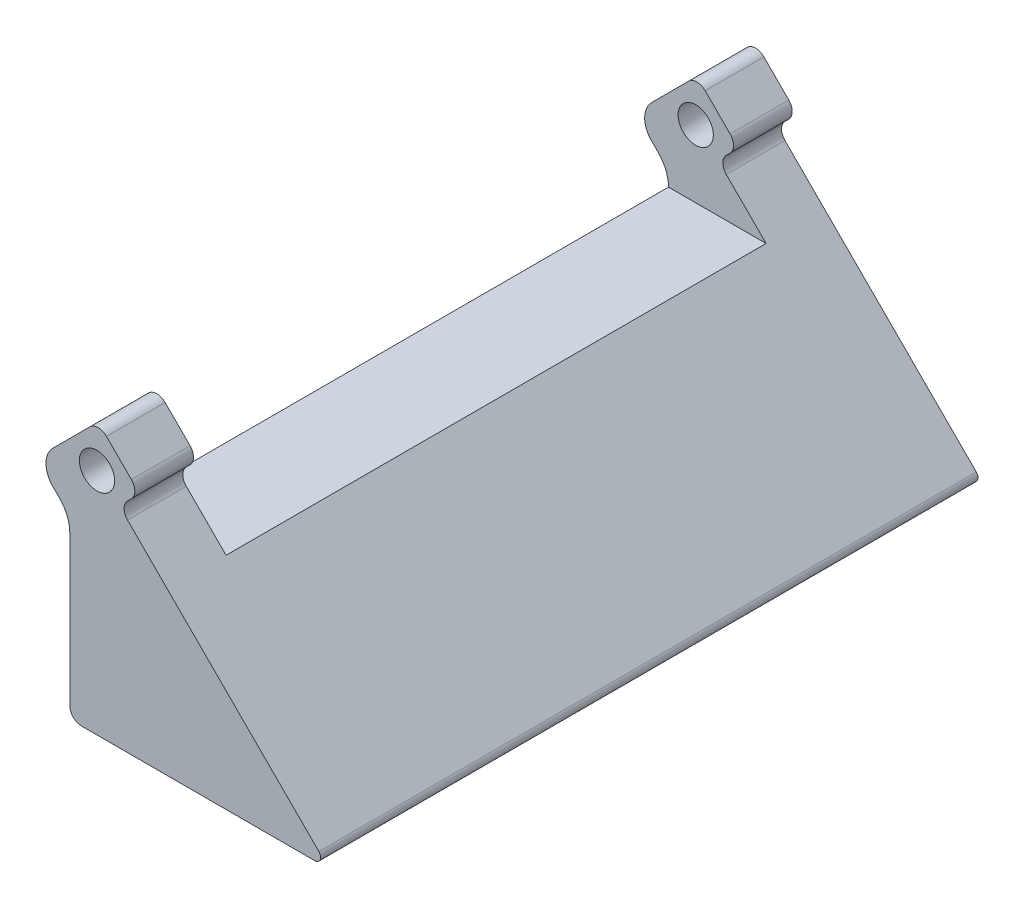
SolidWorks part; units mm, degrees
material "1060-H12"
ref_plane "Front Plane" through (0, 0, 0) normal (0, 0, 1) x (1, 0, 0)
ref_plane "Top Plane" through (0, 0, 0) normal (0, 1, 0) x (1, 0, 0)
ref_plane "Right Plane" through (0, 0, 0) normal (1, 0, 0) x (0, 0, -1)
sketch "Sketch1" plane through (0, 0, 0) normal (0, 0, 1) x (1, 0, 0)
  line L0 (30.0967, -21) -> (76.9648, -21)
  line L1 (-1.3178, -19.5) -> (18.5462, -19.5)
  line L2 (-9.1152, 9.3685) -> (-1.6411, 1.8944)
  line L3 (2.6015, -0.934) -> (2.9274, -0.6081)
  line L4 (2.9274, 0.8061) -> (0.8061, 2.9274)
  line L5 (-0.6081, 2.9274) -> (-1.6411, 1.8944)
  line L6 (-1.6411, 1.8944) -> (-3.7625, -0.2269)
  line L7 (-3.7625, -3.0553) -> (-3.1965, -3.6213)
  line L8 (-2.3178, -5.7426) -> (-2.3178, -18.5)
  line L9 (2.6015, -2.3482) -> (18.8997, -18.6464)
  circle A0 centre (0, 0) radius 1.5
  circle A1 centre (30.0967, 0.35) radius 21.35
  arc A2 (2.9274, -0.6081) -> (2.9274, 0.8061) centre (2.2203, 0.099) ccw
  arc A3 (0.8061, 2.9274) -> (-0.6081, 2.9274) centre (0.099, 2.2203) ccw
  arc A4 (-2.3178, -18.5) -> (-1.3178, -19.5) centre (-1.3178, -18.5) ccw
  arc A5 (2.6015, -0.934) -> (2.6015, -2.3482) centre (3.3086, -1.6411) ccw
  arc A6 (-3.7625, -0.2269) -> (-3.7625, -3.0553) centre (-2.3482, -1.6411) ccw
  arc A7 (18.5462, -19.5) -> (18.8997, -18.6464) centre (18.5462, -19) ccw
  arc A8 (-3.1965, -3.6213) -> (-2.3178, -5.7426) centre (-5.3178, -5.7426) cw
  point P10 (15, -14.7467)
  point P23 (-2.3178, -19.5)
  point P26 (1.8944, -1.6411)
  point P33 (-2.3178, -4.5)
  dimension "D1" = 3
  dimension "D4" = 42.7
  dimension "D12" = 1
  dimension "D13" = 1
  dimension "D14" = 2
  dimension "D15" = 0.5
  dimension "D16" = 3
  dimension "D2" = 21
  dimension "D3" = 1.5
  dimension "D5" = 45
  dimension "D6" = 15
  dimension "D7" = 2.5
  dimension "D8" = 2.5
  dimension "D9" = 15
  dimension "D10" = 5
  dimension "D11" = 2.64
extrude "Boss-Extrude1" add sketch "Sketch1" along normal blind 5 contours L7 A8 L8 A4 L1 A7 L9 A5 L3 A2 L4 A3 L5 L6 A6 A0
sketch "Sketch2" plane through (0, 0, 5) normal (0, 0, 1) x (1, 0, 0)
  line L0 (2.6015, -2.3482) -> (18.8997, -18.6464) construction
  line L1 (-1.3178, -19.5) -> (18.5462, -19.5) construction
  line L2 (-2.3178, -5.7426) -> (-2.3178, -18.5) construction
  line L3 (2.6015, -2.3482) -> (18.8997, -18.6464)
  line L4 (-1.3178, -19.5) -> (18.5462, -19.5)
  line L5 (-2.3178, -5.7426) -> (-2.3178, -18.5)
  line L6 (-2.3178, -5.7426) -> (5.9959, -5.7426)
  arc A0 (18.5462, -19.5) -> (18.8997, -18.6464) centre (18.5462, -19) ccw construction
  arc A1 (-2.3178, -18.5) -> (-1.3178, -19.5) centre (-1.3178, -18.5) ccw construction
  arc A2 (18.5462, -19.5) -> (18.8997, -18.6464) centre (18.5462, -19) ccw
  arc A3 (-2.3178, -18.5) -> (-1.3178, -19.5) centre (-1.3178, -18.5) ccw
  line M4 (-2.3178, -5.7426) -> (-2.3178, -18.5)
  arc M5 (-2.3178, -18.5) -> (-1.3178, -19.5) centre (-1.3178, -18.5) ccw
  line M6 (-1.3178, -19.5) -> (18.5462, -19.5)
  arc M7 (18.5462, -19.5) -> (18.8997, -18.6464) centre (18.5462, -19) ccw
  line M8 (18.8997, -18.6464) -> (2.6015, -2.3482)
extrude "Boss-Extrude2" add sketch "Sketch2" along normal blind 23 contours L6 M4 M5 M6 M7 M8
mirror "Mirror1" about plane through (0, 0, 28) normal (0, 0, 1) of "Boss-Extrude1", "Boss-Extrude2"
